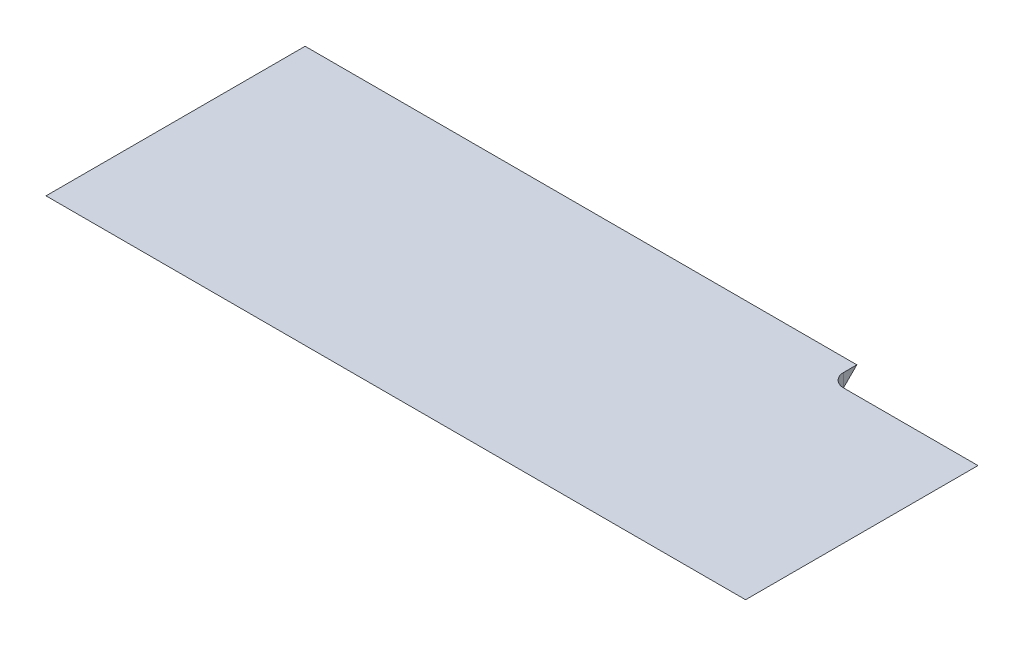
SolidWorks part; units mm, degrees
ref_plane "Front Plane" through (0, 0, 0) normal (0, 0, 1) x (1, 0, 0)
ref_plane "Top Plane" through (0, 0, 0) normal (0, 1, 0) x (1, 0, 0)
ref_plane "Right Plane" through (0, 0, 0) normal (1, 0, 0) x (0, 0, -1)
sketch "Sketch1" plane through (0, 0, 0) normal (0, 1, 0) x (1, 0, 0)
  line L1 (-171.45, 63.5) -> (171.45, 63.5)
  line L2 (-171.45, 63.5) -> (-171.45, -63.5)
  line L3 (-171.45, -63.5) -> (171.45, -63.5)
  line L4 (171.45, 63.5) -> (171.45, -63.5)
  line L5 (-171.45, 63.5) -> (171.45, -63.5) construction
  line L6 (-171.45, -63.5) -> (-171.45, 63.5) construction
  line L8 (-171.45, 63.5) -> (171.45, 63.5) construction
extrude "Boss-Extrude1" add sketch "Sketch1" against normal blind 12.7
draft "Draft1" type of draft neutral plane draft angle 45 faces to draft 4 face at (0, -6.35, -63.5) face at (-171.45, -6.35, 0) face at (171.45, -6.35, 0) face at (0, -6.35, 63.5) neutral plane through (0, 0, 0) neutral plane normal (0, 1, 0) reverse direction yes parameters "D1"=45
sketch "Sketch2" plane through (0, -12.7, 0) normal (0, -1, 0) x (1, 0, 0)
  line L0 (-171.45, 63.5) -> (171.45, 63.5) construction
  line L8 (171.45, -63.5) -> (-171.45, -63.5) construction
  line L9 (0, -63.5) -> (0, 63.5) construction
  line L10 (0.762, 63.5) -> (0.762, -63.5)
  line L11 (24.13, -63.5) -> (0.762, -63.5)
  line L12 (24.13, 63.5) -> (24.13, -63.5)
  line L13 (24.13, 63.5) -> (0.762, 63.5)
extrude "Cut-Extrude1" cut sketch "Sketch2" against normal blind 5.08
sketch "Sketch3" plane through (0, -12.7, 0) normal (0, -1, 0) x (1, 0, 0)
  line L7 (0, -63.5) -> (0, 63.5) construction
  line L8 (171.45, -63.5) -> (-171.45, -63.5) construction
  line L9 (-171.45, 63.5) -> (171.45, 63.5) construction
  line L10 (0.762, 55.88) -> (-19.431, 55.88)
  line L11 (0.762, 30.988) -> (0.762, 55.88)
  line L12 (-6.223, 30.988) -> (0.762, 30.988)
  line L13 (-19.431, 55.88) -> (-19.431, 30.988)
  arc A2 (-19.431, 30.988) -> (-6.223, 30.988) centre (-12.827, 30.988) ccw
extrude "Cut-Extrude2" cut sketch "Sketch3" against normal blind 5.08
sketch "Sketch4" plane through (0, -12.7, 0) normal (0, -1, 0) x (1, 0, 0)
  line L0 (131.1657, -37.719) -> (163.449, -37.719) construction
  line L1 (171.45, -37.338) -> (89.789, -37.338)
  line L2 (171.45, -37.338) -> (171.45, -63.5)
  line L3 (171.45, -63.5) -> (89.789, -63.5)
  line L4 (89.789, -37.338) -> (89.789, -63.5)
  line L6 (90.17, -37.719) -> (90.17, -50.419) construction
  dimension "D1" = 0.381
  dimension "D2" = 0.381
extrude "Cut-Extrude3" cut sketch "Sketch4" against normal blind 5.08
sketch "Sketch5" plane through (0, -12.7, 0) normal (0, -1, 0) x (1, 0, 0)
  line L0 (98.9852, -63.5) -> (98.9852, -50.419)
  line L1 (171.45, -63.5) -> (-171.45, -63.5) construction
  line L2 (98.9852, -50.419) -> (171.45, -50.419)
  line L3 (171.45, 63.5) -> (171.45, -63.5) construction
  line L4 (171.45, -50.419) -> (171.45, -63.5)
  line L5 (171.45, -63.5) -> (98.9852, -63.5)
  line L6 (90.1929, -50.419) -> (112.4639, -50.419) construction
  line L7 (98.9852, -55.499) -> (98.9852, -50.546) construction
extrude "Cut-Extrude4" cut sketch "Sketch5" against normal through all
fillet "Fillet1" radius 6.604 1 edges at (98.9852, -3.81, -50.419)
